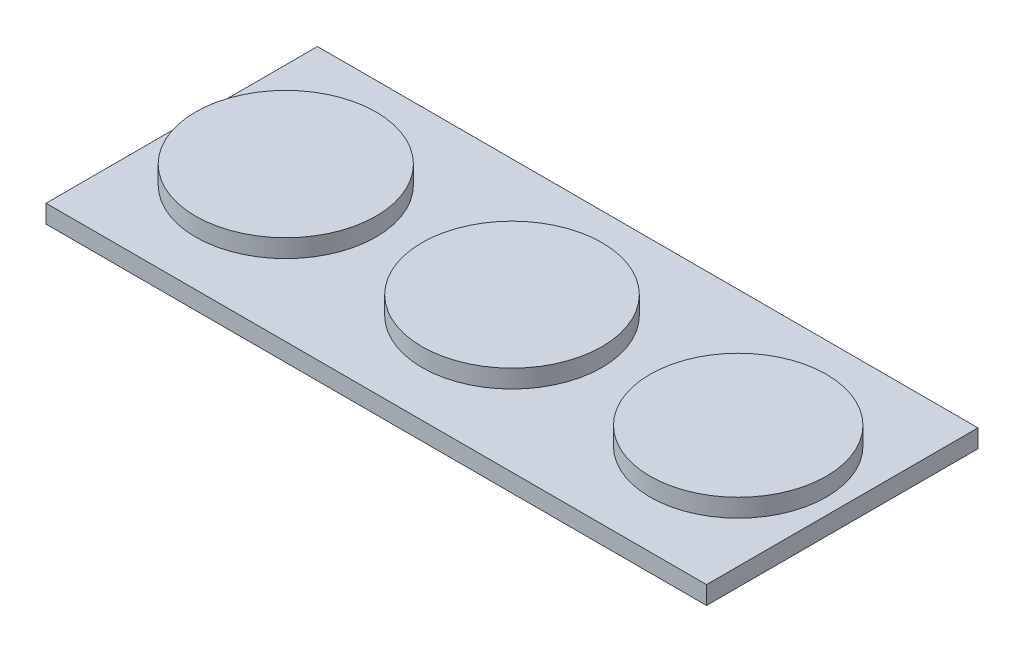
SolidWorks part; units mm, degrees
ref_plane "Alzado" through (0, 0, 0) normal (0, 0, 1) x (1, 0, 0)
ref_plane "Planta" through (0, 0, 0) normal (0, 1, 0) x (1, 0, 0)
ref_plane "Vista lateral" through (0, 0, 0) normal (1, 0, 0) x (0, 0, -1)
sketch "Croquis1" plane through (0, 0, 0) normal (0, 1, 0) x (1, 0, 0)
  line L1 (-36.5, -15) -> (36.5, -15)
  line L2 (-36.5, -15) -> (-36.5, 15)
  line L3 (-36.5, 15) -> (36.5, 15)
  line L4 (36.5, -15) -> (36.5, 15)
  line L5 (-36.5, -15) -> (36.5, 15) construction
  line L6 (-36.5, 15) -> (36.5, -15) construction
  point P0 (0, 0)
  dimension "D1" = 73
  dimension "D2" = 30
extrude "Saliente-Extruir1" add sketch "Croquis1" along normal blind 2
sketch "Croquis2" plane through (0, 2, 0) normal (0, 1, 0) x (1, 0, 0)
  circle A0 centre (-25, 0) radius 9.975
  circle A1 centre (0, 0) radius 9.95
  circle A2 centre (25, 0) radius 9.75
  point P7 (0, 0)
  point P8 (0, 0)
  dimension "D1" = 25
  dimension "D2" = 25
  dimension "D3" = 19.95
  dimension "D4" = 19.5
  dimension "D5" = 19.9
extrude "Saliente-Extruir2" add sketch "Croquis2" along normal blind 2
